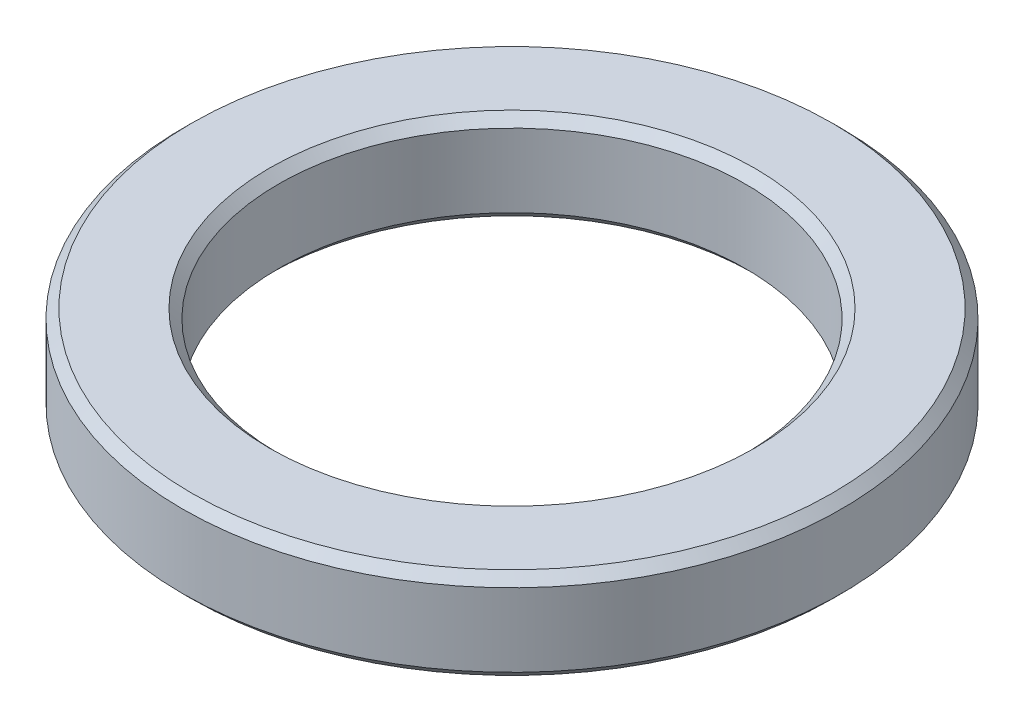
SolidWorks part; units mm, degrees
ref_plane "前视基准面" through (0, 0, 0) normal (0, 0, 1) x (1, 0, 0)
ref_plane "上视基准面" through (0, 0, 0) normal (0, 1, 0) x (1, 0, 0)
ref_plane "右视基准面" through (0, 0, 0) normal (1, 0, 0) x (0, 0, -1)
sketch "草图1" plane through (0, 0, 0) normal (0, 1, 0) x (1, 0, 0)
  circle A0 centre (0, 0) radius 12.75
  circle A1 centre (0, 0) radius 18
  dimension "D1" = 25.5
  dimension "D2" = 36
extrude "凸台-拉伸1" add sketch "草图1" along normal blind 5
chamfer "倒角1" distance 0.5 angle 45 4 edges at (0, 0, 18) (0, 5, 18) (0, 0, 12.75) (0, 5, 12.75)
